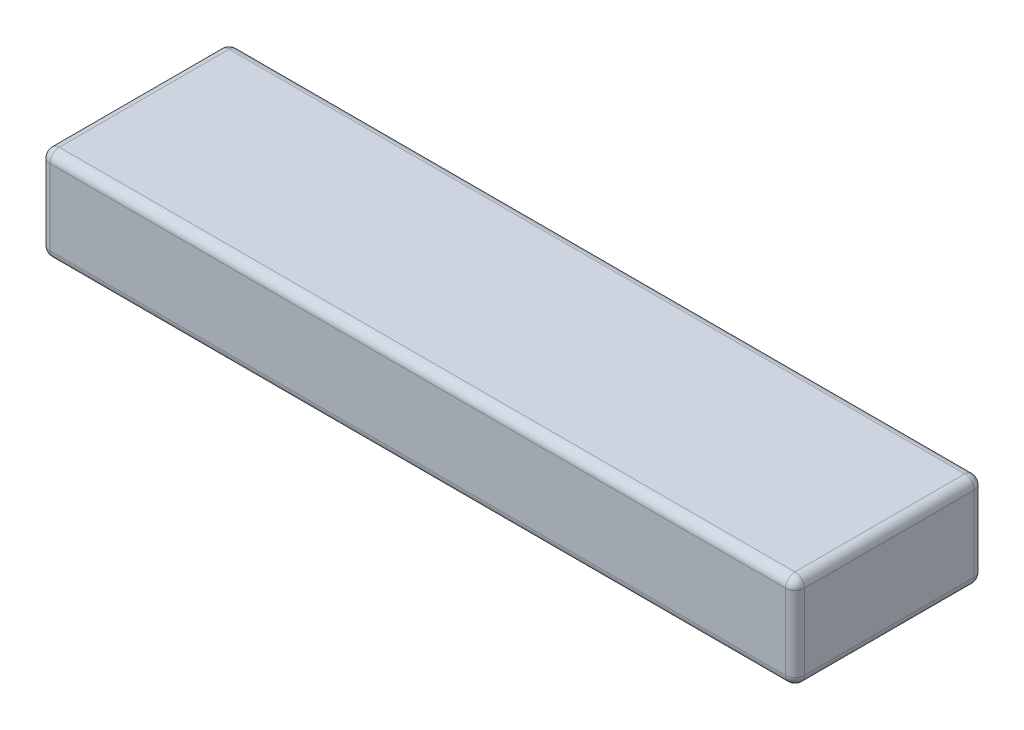
SolidWorks part; units mm, degrees
material "Stainless Steel (ferritic)"
ref_plane "Front Plane" through (0, 0, 0) normal (0, 0, 1) x (1, 0, 0)
ref_plane "Top Plane" through (0, 0, 0) normal (0, 1, 0) x (1, 0, 0)
ref_plane "Right Plane" through (0, 0, 0) normal (1, 0, 0) x (0, 0, -1)
sketch "Sketch1" plane through (0, 0, 0) normal (0, 1, 0) x (1, 0, 0)
  line L1 (20, -5) -> (-20, -5)
  line L2 (20, -5) -> (20, 5)
  line L3 (20, 5) -> (-20, 5)
  line L4 (-20, -5) -> (-20, 5)
  line L5 (20, -5) -> (-20, 5) construction
  line L6 (20, 5) -> (-20, -5) construction
  point P0 (0, 0)
  dimension "D1" = 40
  dimension "D2" = 10
extrude "Boss-Extrude1" add sketch "Sketch1" along normal blind 5
fillet "Fillet1" radius 0.5 12 edges at (20, 2.5, -5) (-20, 2.5, -5) (20, 0, 0) (0, 0, -5) (-20, 0, 0) (-20, 2.5, 5) (20, 2.5, 5) (0, 0, 5) (0, 5, -5) (20, 5, 0) (0, 5, 5) (-20, 5, 0)
